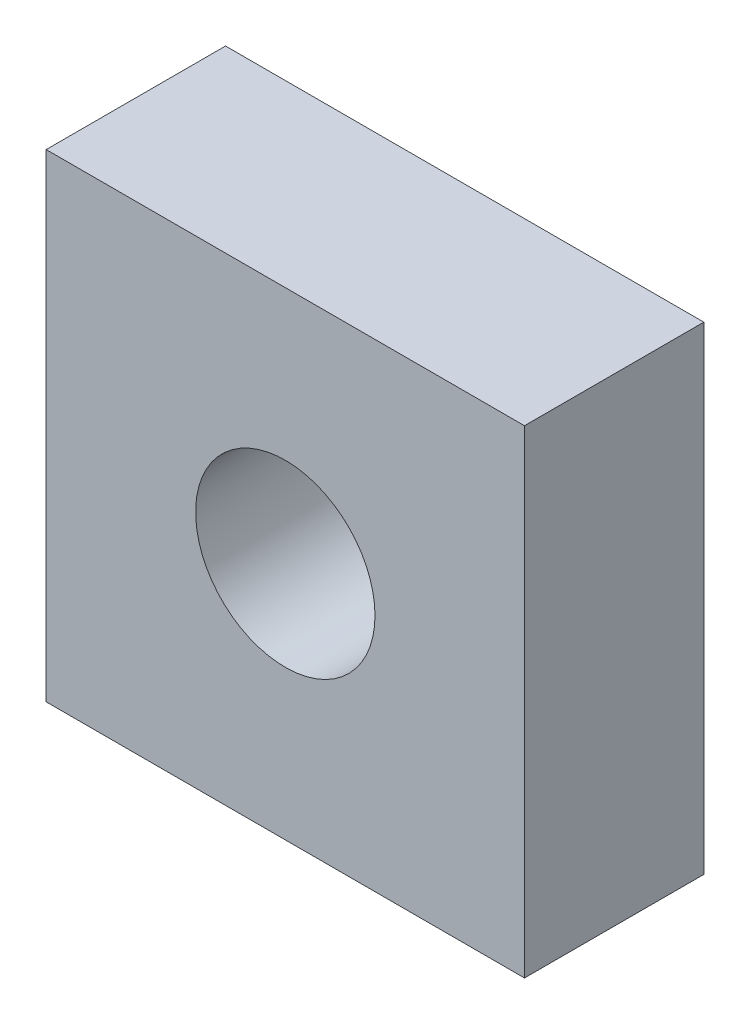
SolidWorks part; units mm, degrees
ref_plane "Спереди" through (0, 0, 0) normal (0, 0, 1) x (1, 0, 0)
ref_plane "Сверху" through (0, 0, 0) normal (0, 1, 0) x (1, 0, 0)
ref_plane "Справа" through (0, 0, 0) normal (1, 0, 0) x (0, 0, -1)
other "Configuration Table"
sketch "Эскиз1" plane through (0, 0, 0) normal (0, 0, 1) x (1, 0, 0)
  line L0 (4, 8) -> (4, 0) construction
  line L1 (0, 0) -> (8, 0)
  line L2 (0, 0) -> (0, 8)
  line L3 (0, 8) -> (8, 8)
  line L4 (8, 0) -> (8, 8)
  line L5 (0, 4) -> (8, 4) construction
  dimension "D1" = 8
  dimension "D2" = 8
extrude "Бобышка-Вытянуть1" add sketch "Эскиз1" along normal blind 3
sketch "Эскиз2" plane through (0, 0, 3) normal (0, 0, 1) x (1, 0, 0)
  line L0 (0, 0) -> (8, 0) construction
  line L1 (0, 8) -> (0, 0) construction
  circle A0 centre (4, 4) radius 1.5
  dimension "D1" = 3
  dimension "D2" = 4
  dimension "D3" = 4
extrude "Вырез-Вытянуть1" cut sketch "Эскиз2" against normal through all
